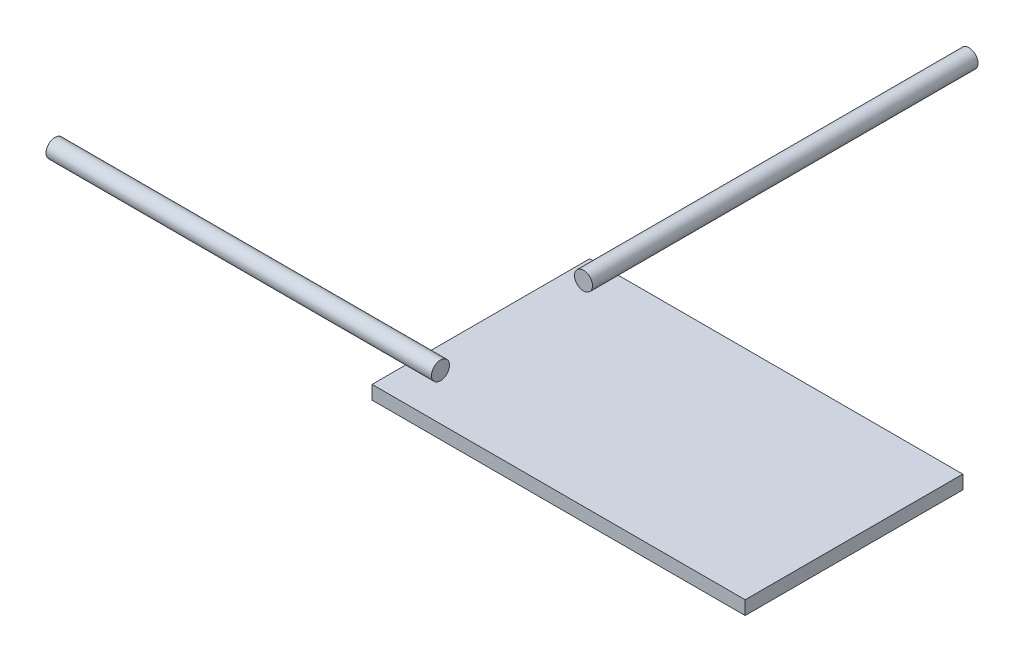
SolidWorks part; units mm, degrees
ref_plane "Front Plane" through (0, 0, 0) normal (0, 0, 1) x (1, 0, 0)
ref_plane "Top Plane" through (0, 0, 0) normal (0, 1, 0) x (1, 0, 0)
ref_plane "Right Plane" through (0, 0, 0) normal (1, 0, 0) x (0, 0, -1)
sketch "Sketch1" plane through (0, 0, 0) normal (0, 1, 0) x (1, 0, 0)
  line L1 (15, 8.75) -> (-15, 8.75)
  line L2 (15, 8.75) -> (15, -8.75)
  line L3 (15, -8.75) -> (-15, -8.75)
  line L4 (-15, 8.75) -> (-15, -8.75)
  line L5 (15, 8.75) -> (-15, -8.75) construction
  line L6 (15, -8.75) -> (-15, 8.75) construction
  point P0 (0, 0)
  dimension "D1" = 17.5
  dimension "D2" = 30
extrude "Boss-Extrude1" add sketch "Sketch1" along normal blind 1.1
sketch "Sketch2" plane through (0, 0, -8.75) normal (0, 0, -1) x (-1, 0, 0)
  line L0 (-15, 1.1) -> (15, 1.1) construction
  line L1 (15, 1.1) -> (15, 0) construction
  circle A0 centre (13, 1.825) radius 0.725
  dimension "D1" = 1.45
  dimension "D2" = 2
extrude "Boss-Extrude2" add sketch "Sketch2" along normal blind 28.5 separate body
sketch "Sketch4" plane through (-15, 0, 0) normal (-1, 0, 0) x (0, 0, 1)
  line L0 (-8.75, 1.1) -> (8.75, 1.1) construction
  line L2 (-8.75, 2.55) -> (-37.25, 2.55) construction
  line L3 (8.75, 1.1) -> (8.75, 0) construction
  circle A0 centre (5.75, 1.825) radius 0.725
  dimension "D1" = 3
extrude "Boss-Extrude3" add sketch "Sketch4" along normal blind 28.5 separate body
sketch "Sketch6" plane through (0, 0, -8.75) normal (0, 0, 1) x (1, 0, 0)
  circle A1 centre (-13, 1.825) radius 0.725
  circle A2 centre (-13, 1.825) radius 0.725
  dimension "D1" = 0
extrude "Boss-Extrude4" add sketch "Sketch6" along normal blind 2.5
sketch "Sketch7" plane through (-15, 0, 0) normal (1, 0, 0) x (0, 0, -1)
  circle A1 centre (-5.75, 1.825) radius 0.725
  circle A2 centre (-5.75, 1.825) radius 0.725
  dimension "D1" = 0
extrude "Boss-Extrude5" add sketch "Sketch7" along normal blind 2.5
